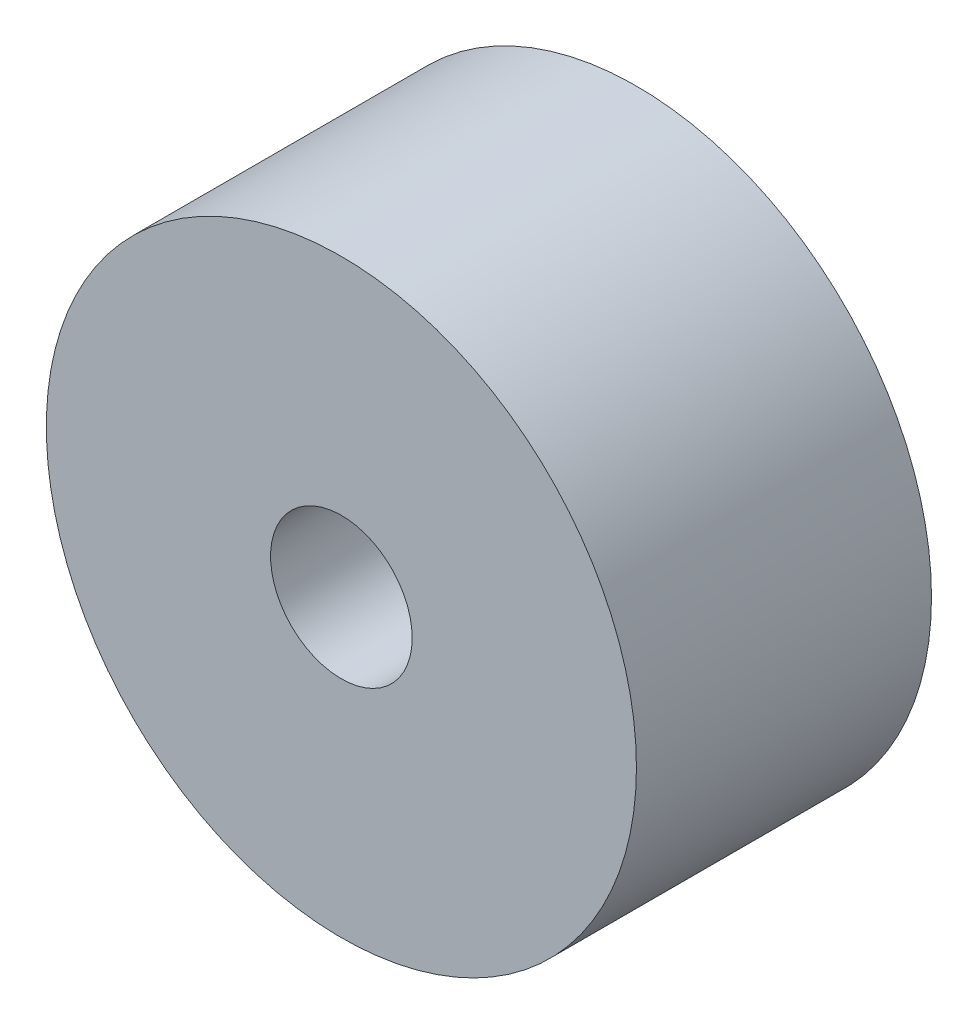
SolidWorks part; units mm, degrees
ref_plane "Front Plane" through (0, 0, 0) normal (0, 0, 1) x (1, 0, 0)
ref_plane "Top Plane" through (0, 0, 0) normal (0, 1, 0) x (1, 0, 0)
ref_plane "Right Plane" through (0, 0, 0) normal (1, 0, 0) x (0, 0, -1)
sketch "Sketch1" plane through (0, 0, 0) normal (0, 0, 1) x (1, 0, 0)
  circle A0 centre (0, 0) radius 5
  circle A1 centre (0, 0) radius 1.2
  dimension "D1" = 2.4
  dimension "D2" = 10
extrude "Boss-Extrude1" add sketch "Sketch1" along normal blind 5
